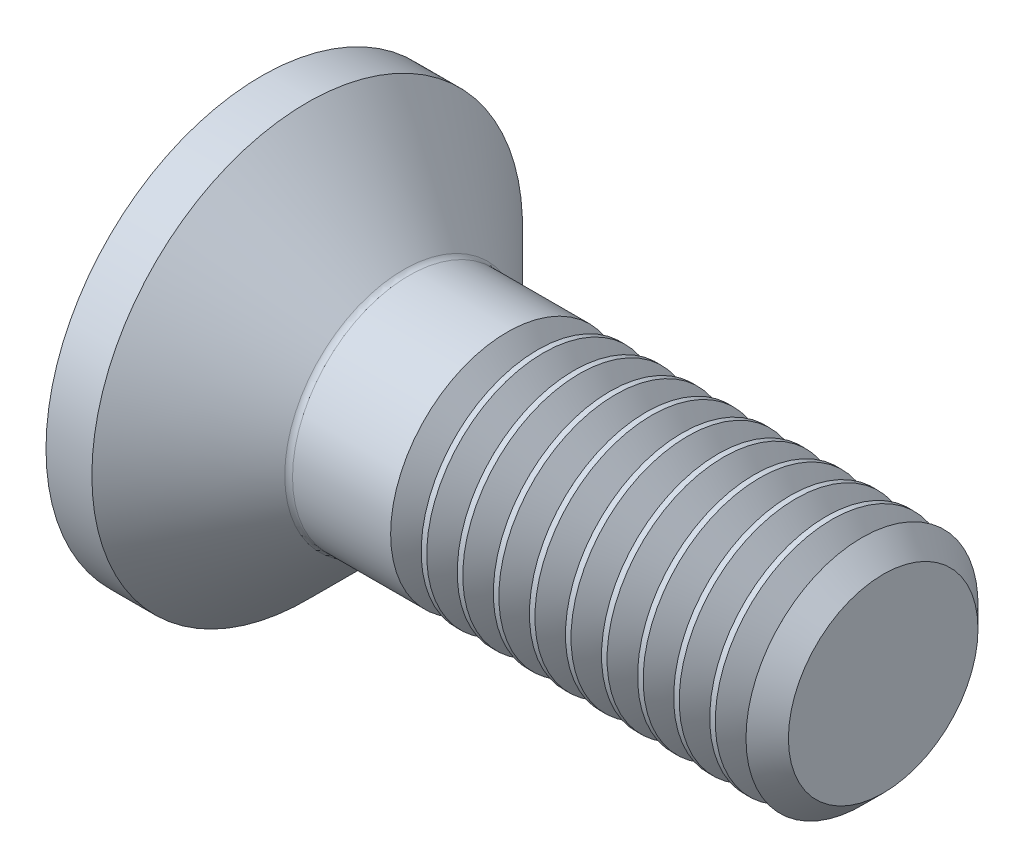
SolidWorks part; units mm, degrees
ref_plane "Plane1" through (0, 0, 0) normal (0, 0, 1) x (1, 0, 0)
ref_plane "Plane2" through (0, 0, 0) normal (0, 1, 0) x (1, 0, 0)
ref_plane "Plane3" through (0, 0, 0) normal (1, 0, 0) x (0, 0, -1)
sketch "BodySke" plane through (0, 0, 0) normal (0, 0, 1) x (1, 0, 0)
  line L0 (0, 0) -> (0, 2.77)
  line L1 (0.59, 2.77) -> (1.86, 1.5)
  line L2 (0, 2.77) -> (0.59, 2.77)
  line L3 (1.86, 1.5) -> (7.7195, 1.5)
  line L4 (8, 1.2195) -> (8, 0)
  line L5 (8, 0) -> (0, 0)
  line L6 (0, 0) -> (127, 0) construction
  line L7 (0.59, -2.77) -> (1.86, -1.5) construction
  line L8 (8, 1.2195) -> (7.7195, 1.5)
  line L9 (0, -2.77) -> (0.59, -2.77) construction
  line L10 (8, -1.2195) -> (7.7195, -1.5) construction
  line L11 (2.36, 7.85) -> (2.36, -14.375) construction
  line L12 (0, 19.05) -> (0, -3.175) construction
  dimension "D1" = 0.59
  dimension "Diameter" = 3
  dimension "Head_ht" = 1.86
  dimension "Length" = 8
  dimension "Body_ch_ang" = 45
  dimension "Head_dia" = 5.54
  dimension "Minor_dia" = 2.439
  dimension "Head_ang" = 90
  dimension "Advance" = 0.5
  dimension "Thread_nom" = 8
revolve "BaseBody" add sketch "BodySke"
cosmetic thread "ThreadCosmetic" [suppressed]
fillet "Fillet1" radius 0.1 1 edges at (1.86, 0, 1.5)
sketch "Sketch2" plane through (0, 0, 0) normal (0, 0, 1) x (1, 0, 0)
  line L0 (0, 1) -> (1.1, 1)
  line L1 (1.1, 1) -> (1.6774, 0)
  line L2 (0, 0) -> (127, 0) construction
  line L3 (1.6774, 0) -> (0, 0)
  line L4 (0, 0) -> (0, 1)
  line L5 (0, -1) -> (1.1, -1) construction
  line L6 (0, 0) -> (47.625, 0) construction
  line L8 (0, 2.77) -> (0, -2.77) construction
  dimension "D2" = 60
  dimension "PreBroach_depth" = 1.1
  dimension "PreBroach_dia" = 2
revolve "PreBroach" cut sketch "Sketch2" angle 360 about L6
sketch "Sketch3" plane through (0, 0, 0) normal (-1, 0, 0) x (0, 0, 1)
  line L0 (-1, -0.5774) -> (-1, 0.5774)
  line L1 (-1, 0.5774) -> (0, 1.1547)
  line L2 (0, 1.1547) -> (1, 0.5774)
  line L3 (1, 0.5774) -> (1, -0.5774)
  line L4 (1, -0.5774) -> (0, -1.1547)
  line L5 (0, -1.1547) -> (-1, -0.5774)
  dimension "D1" = 1
  dimension "D2" = 1
  dimension "D3" = 2
  dimension "Hex_size" = 2
extrude "Hex" cut sketch "Sketch3" against normal blind 1.1
sketch "ThdSchSke" plane through (0, 0, 0) normal (0, 0, 1) x (1, 0, 0)
  line L0 (3.36, -1.2195) -> (3.1636, -1.5)
  line L1 (3.36, -1.2195) -> (3.5564, -1.5)
  line L2 (3.5564, -1.5) -> (3.5564, -1.875)
  line L3 (-3.175, 0) -> (5.1513, 0) construction
  line L4 (0, 2.77) -> (0, -2.77) construction
  line L5 (3.5564, -1.875) -> (3.1636, -1.875)
  line L6 (3.1636, -1.875) -> (3.1636, -1.5)
  dimension "Thread_minor" = 2.439
  dimension "Diameter" = 3
  dimension "Start" = 3.36
  dimension "SideAngle" = 55
  dimension "VeeAngle" = 70
  dimension "Overcut" = 3.75
revolve "ThreadSchematic" cut sketch "ThdSchSke" angle 360 about L3
pattern_linear "ThdSchPat" count 10 spacing 0.464 along (1, 0, 0) of "ThreadSchematic"
equation "\"Thread_minor@ThreadCosmetic\"  =  \"Minor_dia@BodySke\""
equation "\"D1@Sketch3\" = \"Hex_size@Sketch3\" / 2"
equation "\"D2@Sketch3\" = \"D1@Sketch3\""
equation "\"D3@Sketch3\" = \"Hex_size@Sketch3\""
equation "\"Thread_length@ThreadCosmetic\" = ((sgn( (\"Length@BodySke\" - \"Advance@BodySke\" * 3.0 - \"Head_ht@BodySke\" ) - \"Thread_nom@BodySke\" )-1)*( (\"Length@BodySke\" - \"Advance@BodySke\" * 3.0 - \"Head_ht@BodySke\" ) - \"Thread_nom@BodySke\" ))/-2+ \"Thread_nom@BodySke\""
equation "\"Thread_minor@ThdSchSke\" = \"Minor_dia@BodySke\""
equation "\"Diameter@ThdSchSke\" = \"Diameter@BodySke\""
equation "\"Overcut@ThdSchSke\" = \"Diameter@BodySke\" * 1.25"
equation "\"Start@ThdSchSke\" = 0.000001 + \"Length@BodySke\" - \"Thread_length@ThreadCosmetic\"  '---Countersunk---"
equation "\"Num_threads@ThdSchPat\" = int( \"Thread_length@ThreadCosmetic\" / \"Advance@BodySke\" + 0.999 )  + 1"
equation "\"Advance@ThdSchPat\" = \"Thread_length@ThreadCosmetic\" /  (\"Num_threads@ThdSchPat\" - 1) 'relax it"
equation "\"Num_threads@ThdSchPat\" = \"Num_threads@ThdSchPat\" - sgn( \"Num_threads@ThdSchPat\" - 1) '---chamfered tips only---"
